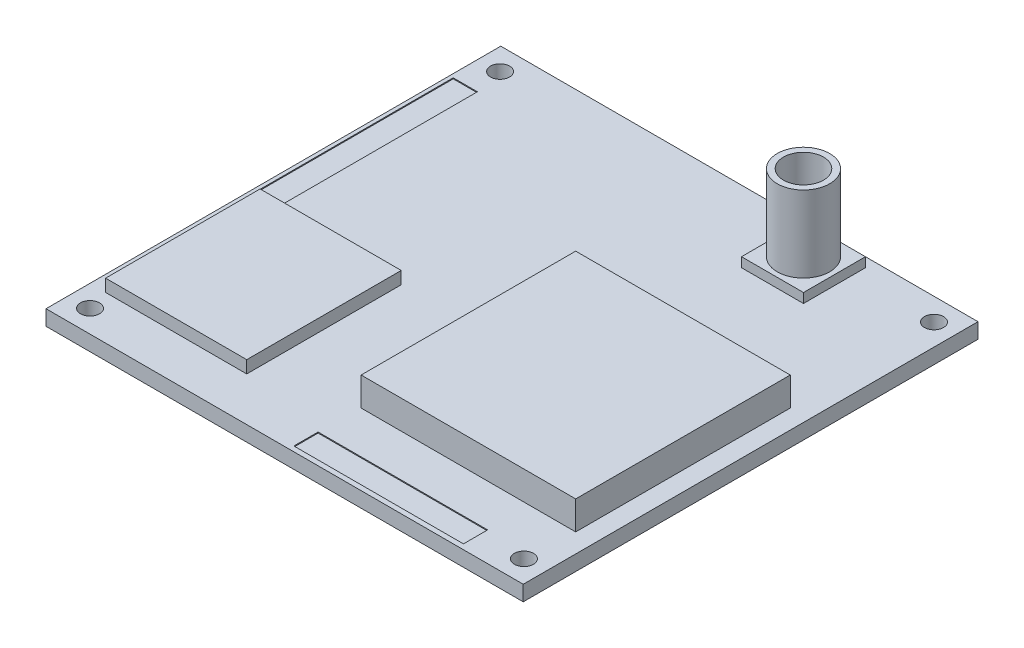
SolidWorks part; units mm, degrees
ref_plane "前视基准面" through (0, 0, 0) normal (0, 0, 1) x (1, 0, 0)
ref_plane "上视基准面" through (0, 0, 0) normal (0, 1, 0) x (1, 0, 0)
ref_plane "右视基准面" through (0, 0, 0) normal (1, 0, 0) x (0, 0, -1)
sketch "草图2" plane through (0, 0, 0) normal (0, 1, 0) x (1, 0, 0)
  line L0 (0, 46.3352) -> (0, -52.1538) construction
  line L1 (-57.7528, 0) -> (64.2708, 0) construction
  line L2 (-25.0215, 23.8435) -> (25.0215, 23.8435)
  line L3 (-25.0215, 23.8435) -> (-25.0215, -23.8435)
  line L4 (-25.0215, -23.8435) -> (25.0215, -23.8435)
  line L5 (25.0215, 23.8435) -> (25.0215, -23.8435)
  dimension "D1" = 50.043
  dimension "D2" = 47.687
extrude "凸台-拉伸1" add sketch "草图2" along normal blind 1.6
sketch "草图3" plane through (0, 1.6, 0) normal (0, 1, 0) x (1, 0, 0)
  line L0 (-34.3672, 0) -> (35.573, 0) construction
  line L1 (0, 29.9457) -> (0, -29.4097) construction
  circle A0 centre (-22.75, 21.5) radius 1
  circle A1 centre (22.75, 21.5) radius 1
  circle A2 centre (22.75, -21.5) radius 1
  circle A3 centre (-22.75, -21.5) radius 1
  dimension "D1" = 2
  dimension "D2" = 43
  dimension "D3" = 45.5
extrude "切除-拉伸1" cut sketch "草图3" against normal blind 1.6
sketch "草图4" plane through (0, 1.6, 0) normal (0, 1, 0) x (1, 0, 0)
  line L0 (-25.0215, -23.8435) -> (25.0215, -23.8435) construction
  line L1 (23.0215, -16.3435) -> (0.5215, -16.3435)
  line L2 (23.0215, -16.3435) -> (23.0215, 6.1565)
  line L3 (23.0215, 6.1565) -> (0.5215, 6.1565)
  line L4 (0.5215, -16.3435) -> (0.5215, 6.1565)
  line L5 (25.0215, -23.8435) -> (25.0215, 23.8435) construction
  dimension "D1" = 7.5
  dimension "D2" = 2
  dimension "D3" = 22.5
  dimension "D4" = 22.5
extrude "凸台-拉伸2" add sketch "草图4" along normal blind 3
sketch "草图5" plane through (0, 1.6, 0) normal (0, 1, 0) x (1, 0, 0)
  line L0 (-25.0215, 23.8435) -> (-25.0215, -23.8435) construction
  line L1 (-8.5715, -19.2435) -> (-23.3715, -19.2435)
  line L2 (-8.5715, -19.2435) -> (-8.5715, -3.0435)
  line L3 (-8.5715, -3.0435) -> (-23.3715, -3.0435)
  line L4 (-23.3715, -19.2435) -> (-23.3715, -3.0435)
  line L5 (-25.0215, -23.8435) -> (25.0215, -23.8435) construction
  dimension "D1" = 1.65
  dimension "D2" = 4.6
  dimension "D3" = 14.8
  dimension "D4" = 16.2
extrude "凸台-拉伸3" add sketch "草图5" along normal blind 1.3
sketch "草图6" plane through (0, 1.6, 0) normal (0, 1, 0) x (1, 0, 0)
  line L1 (-24.6415, 18.4765) -> (-22.1015, 18.4765)
  line L2 (-24.6415, 18.4765) -> (-24.6415, -1.8435)
  line L3 (-24.6415, -1.8435) -> (-22.1015, -1.8435)
  line L4 (-22.1015, 18.4765) -> (-22.1015, -1.8435)
  line L5 (-25.0215, -23.8435) -> (25.0215, -23.8435) construction
  line L6 (-9.731, -22.0435) -> (19.5007, -22.0435) construction
  line L7 (0.4415, -20.7735) -> (18.2215, -20.7735)
  line L8 (0.4415, -20.7735) -> (0.4415, -23.3135)
  line L9 (0.4415, -23.3135) -> (18.2215, -23.3135)
  line L10 (18.2215, -20.7735) -> (18.2215, -23.3135)
  line L11 (-23.3715, 19.6558) -> (-23.3715, -6.3969) construction
  line L12 (-25.0215, 23.8435) -> (-25.0215, -23.8435) construction
  line L13 (25.0215, -23.8435) -> (25.0215, 23.8435) construction
  dimension "D1" = 2.54
  dimension "D2" = 1.65
  dimension "D3" = 22
  dimension "D4" = 20.32
  dimension "D5" = 2.54
  dimension "D6" = 17.78
  dimension "D7" = 1.8
  dimension "D8" = 6.8
extrude "切除-拉伸2" cut sketch "草图6" against normal blind 0.1
sketch "草图7" plane through (0, 1.6, 0) normal (0, 1, 0) x (1, 0, 0)
  line L0 (25.0215, 23.8435) -> (-25.0215, 23.8435) construction
  line L1 (7.7215, 22.8435) -> (14.2215, 22.8435)
  line L2 (7.7215, 22.8435) -> (7.7215, 16.3435)
  line L3 (7.7215, 16.3435) -> (14.2215, 16.3435)
  line L4 (14.2215, 22.8435) -> (14.2215, 16.3435)
  line L5 (25.0215, -23.8435) -> (25.0215, 23.8435) construction
  dimension "D1" = 1
  dimension "D2" = 10.8
  dimension "D3" = 6.5
  dimension "D4" = 6.5
extrude "凸台-拉伸4" add sketch "草图7" along normal blind 1
sketch "草图8" plane through (0, 2.6, 0) normal (0, 1, 0) x (1, 0, 0)
  line L0 (5.344, 19.5935) -> (17.6018, 19.5935) construction
  line L1 (10.9715, 26.8105) -> (10.9715, 12.7652) construction
  line L2 (7.7215, 22.8435) -> (7.7215, 16.3435) construction
  line L3 (14.2215, 16.3435) -> (14.2215, 22.8435) construction
  line L4 (7.7215, 16.3435) -> (14.2215, 16.3435) construction
  line L5 (14.2215, 22.8435) -> (7.7215, 22.8435) construction
  circle A0 centre (10.9715, 19.5935) radius 2.75
  dimension "D1" = 5.5
extrude "凸台-拉伸5" add sketch "草图8" along normal blind 8
sketch "草图9" plane through (0, 10.6, 0) normal (0, 1, 0) x (1, 0, 0)
  circle A0 centre (10.9715, 19.5935) radius 2.1
  dimension "D1" = 4.2
extrude "切除-拉伸3" cut sketch "草图9" against normal blind 3
